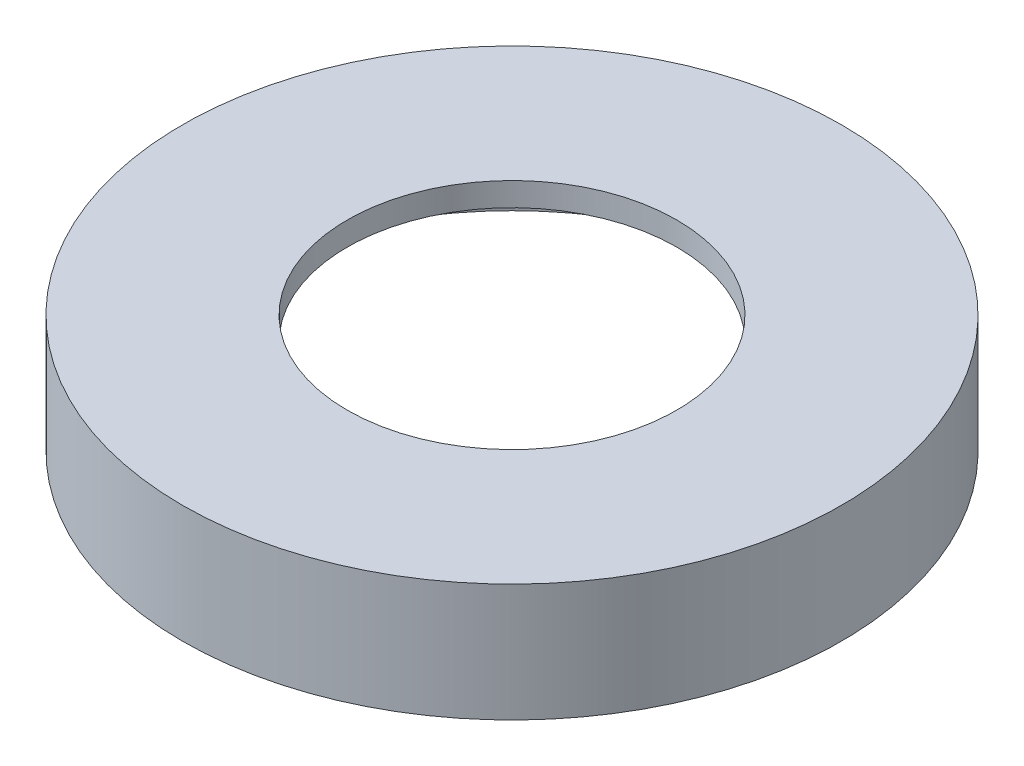
SolidWorks part; units mm, degrees
ref_plane "前视基准面" through (0, 0, 0) normal (0, 0, 1) x (1, 0, 0)
ref_plane "上视基准面" through (0, 0, 0) normal (0, 1, 0) x (1, 0, 0)
ref_plane "右视基准面" through (0, 0, 0) normal (1, 0, 0) x (0, 0, -1)
other "Configuration Table"
sketch "草图2" plane through (0, 0, 0) normal (0, 0, 1) x (1, 0, 0)
  line L0 (0, 0) -> (0, 15.8607) construction
  line L1 (0, 5) -> (14, 5)
  line L2 (14, 5) -> (14, 0)
  line L3 (14, 0) -> (12.5, 0)
  line L4 (12.5, 0) -> (12.5, 4)
  line L5 (12.5, 4) -> (0, 4)
  line L6 (0, 5) -> (0, 4)
  dimension "D1" = 12.5
  dimension "D2" = 4
  dimension "D3" = 1
  dimension "D4" = 1.5
revolve "旋转1" add sketch "草图2" angle 360 about L0
sketch "草图3" plane through (0, 4, 0) normal (0, -1, 0) x (1, 0, 0)
  circle A0 centre (0, 0) radius 7
  dimension "D1" = 14
extrude "切除-拉伸1" cut sketch "草图3" against normal blind 10
